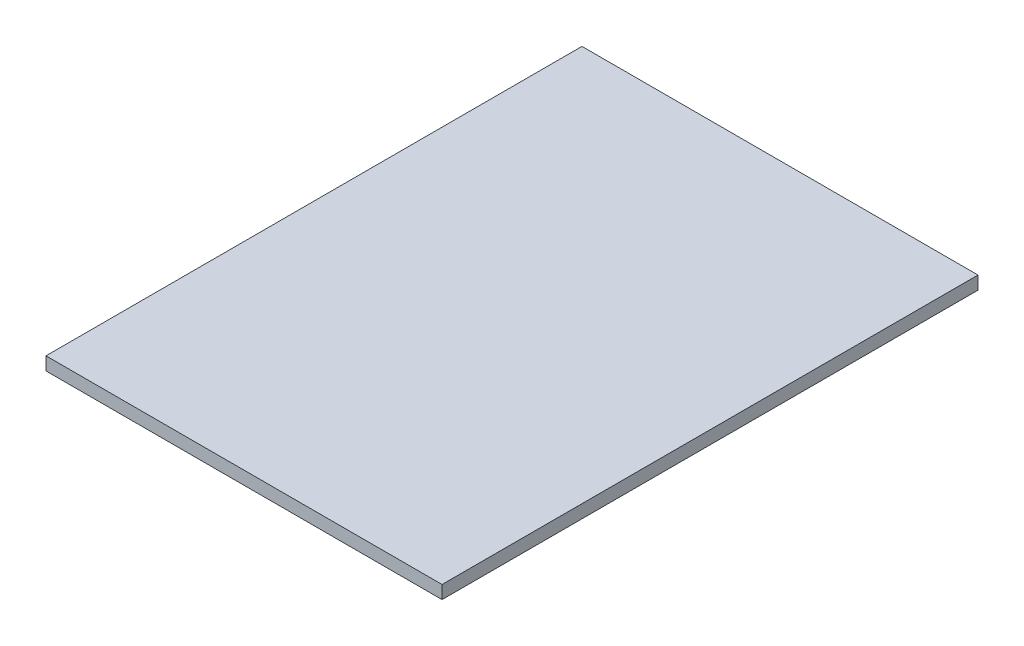
SolidWorks part; units mm, degrees
ref_plane "Front Plane" through (0, 0, 0) normal (0, 0, 1) x (1, 0, 0)
ref_plane "Top Plane" through (0, 0, 0) normal (0, 1, 0) x (1, 0, 0)
ref_plane "Right Plane" through (0, 0, 0) normal (1, 0, 0) x (0, 0, -1)
sketch "Sketch1" plane through (0, 0, 0) normal (0, 1, 0) x (1, 0, 0)
  line L1 (-86.7948, -106.2332) -> (64.192, -106.2332)
  line L2 (-86.7948, -106.2332) -> (-86.7948, 98.0962)
  line L3 (-86.7948, 98.0962) -> (64.192, 98.0962)
  line L4 (64.192, -106.2332) -> (64.192, 98.0962)
  line L5 (-86.7948, -106.2332) -> (64.192, 98.0962) construction
  line L6 (-86.7948, 98.0962) -> (64.192, -106.2332) construction
  point P0 (-11.3014, -4.0685)
extrude "Boss-Extrude1" add sketch "Sketch1" along normal blind 5
